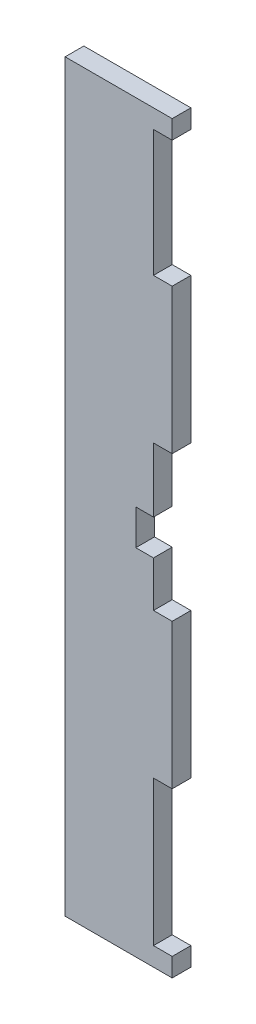
SolidWorks part; units mm, degrees
ref_plane "Front Plane" through (0, 0, 0) normal (0, 0, 1) x (1, 0, 0)
ref_plane "Top Plane" through (0, 0, 0) normal (0, 1, 0) x (1, 0, 0)
ref_plane "Right Plane" through (0, 0, 0) normal (1, 0, 0) x (0, 0, -1)
sketch "Sketch1" plane through (0, 0, 0) normal (0, 0, 1) x (1, 0, 0)
  line L1 (0, 3.175) -> (15, 3.175)
  line L2 (0, 3.175) -> (0, 129.525)
  line L13 (0, 129.525) -> (15, 129.525)
  line L33 (18.175, 6.35) -> (18.175, 3.175) construction
  line L34 (18.175, 129.525) -> (15, 129.525) construction
  line L35 (18.175, 6.35) -> (15, 6.35) construction
  line L36 (18.175, 126.35) -> (15, 126.35) construction
  line L37 (18.175, 129.525) -> (18.175, 126.35) construction
  line L38 (18.175, 3.175) -> (15, 3.175)
  line L40 (18.175, 6.35) -> (18.175, 3.175)
  line L42 (18.175, 6.35) -> (15, 6.35)
  line L44 (18.175, 126.35) -> (15, 126.35)
  line L46 (18.175, 3.175) -> (15, 3.175) construction
  line L47 (18.175, 129.525) -> (18.175, 126.35)
  line L48 (18.175, 129.525) -> (15, 129.525)
  line L53 (15, 6.35) -> (15, 30.985) construction
  line L54 (18.175, 30.985) -> (15, 30.985) construction
  line L55 (18.175, 30.985) -> (18.175, 55.62) construction
  line L56 (18.175, 55.62) -> (15, 55.62) construction
  line L57 (15, 55.62) -> (15, 80.255) construction
  line L58 (18.175, 80.255) -> (15, 80.255) construction
  line L59 (18.175, 80.255) -> (18.175, 104.89) construction
  line L60 (18.175, 104.89) -> (15, 104.89) construction
  line L61 (15, 104.89) -> (15, 126.35) construction
  line L63 (15, 6.35) -> (15, 30.985)
  line L64 (18.175, 30.985) -> (15, 30.985)
  line L65 (18.175, 30.985) -> (18.175, 55.62)
  line L66 (18.175, 55.62) -> (15, 55.62)
  line L67 (15, 55.62) -> (15, 80.255)
  line L68 (18.175, 80.255) -> (15, 80.255)
  line L69 (18.175, 80.255) -> (18.175, 104.89)
  line L70 (18.175, 104.89) -> (15, 104.89)
  line L71 (15, 104.89) -> (15, 126.35)
  dimension "D1" = 15
extrude "Boss-Extrude1" add sketch "Sketch1" along normal blind 3.175
sketch "Sketch2" plane through (0, 0, 0) normal (0, 0, -1) x (-1, 0, 0)
  line L0 (-15, 126.35) -> (-15, 6.35) construction
  line L6 (-12, 69.35) -> (-15, 69.35)
  line L7 (-12, 69.35) -> (-12, 63.35)
  line L8 (-12, 63.35) -> (-15, 63.35)
  line L9 (-15, 69.35) -> (-15, 63.35)
  point P6 (-15, 66.35)
  point P7 (-15, 66.35)
  dimension "D1" = 6
  dimension "D2" = 3
extrude "Cut-Extrude2" cut sketch "Sketch2" against normal up to next
